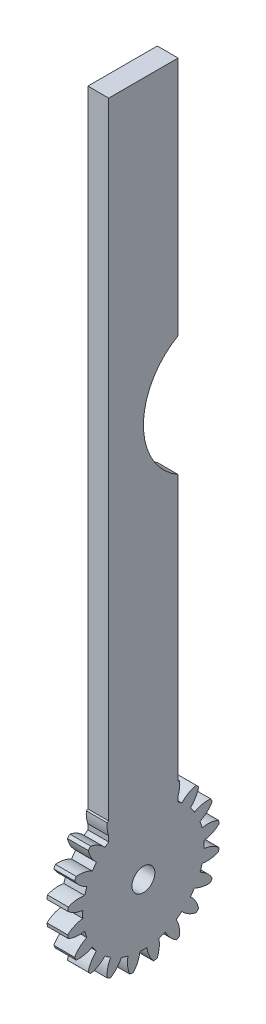
SolidWorks part; units mm, degrees
ref_plane "Plane1" through (0, 0, 0) normal (0, 0, 1) x (1, 0, 0)
ref_plane "Plane2" through (0, 0, 0) normal (0, 1, 0) x (1, 0, 0)
ref_plane "Plane3" through (0, 0, 0) normal (1, 0, 0) x (0, 0, -1)
sketch "HoldingSke" plane through (0, 0, 0) normal (0, 1, 0) x (1, 0, 0)
  line L0 (0, 0) -> (0.9397, -0.342)
  line L1 (-15, 0) -> (100, 0) construction
  line L2 (0, 0) -> (-2.1039, 2.3779)
  line L3 (0, 0) -> (-11.863, 4.5341)
  line L4 (0, 0) -> (8.1152, 2.9537)
  line L5 (0, 0) -> (-46.8476, -17.4728)
  line L6 (0, 0) -> (-2.4869, -1.6779)
  line L7 (-2.1039, 2.3779) -> (8.6586, 51.2059)
  line L8 (-76.2, 54.61) -> (-75.3, 54.61)
  line L9 (-71.009, 38.7566) -> (-53.1078, 45.2721)
  line L10 (-76.2, 71.12) -> (104.1128, 71.12)
  line L11 (0, 0) -> (-3, 0)
  line L12 (-76.2, 101.6) -> (-76.162, 101.6)
  line L13 (24.9733, 27.94) -> (52.9518, 28.4284)
  line L14 (24.9733, 27.94) -> (24.9743, 27.94)
  line L15 (24.9733, 27.94) -> (100.4006, 29.5858)
  line L16 (-63.627, -1) -> (-12.827, -1)
  circle A0 centre (0, 0) radius 2.5
  circle A1 centre (0, 0) radius 8.749
  circle A2 centre (0, 0) radius 37.5
  circle A3 centre (0, 0) radius 2.5
  dimension "MHD" = 17.498
  dimension "Hub_dia" = 75
  dimension "Bore" = 5
  dimension "MBD" = 5
  dimension "Num_teeth" = 20
  dimension "Pitch" = 1
  dimension "Overall_len" = 50
  dimension "Show_teeth" = 20
  dimension "Thickness" = 3
  dimension "OAL" = 50.0001
  dimension "T_dim" = 0.9
  dimension "Ap" = 20
  dimension "H" = 19.05
  dimension "Pitch_radius" = 180.3128
  dimension "Width" = 3
  dimension "Backlash" = 0.038
  dimension "Addendum_fac" = 1
  dimension "Dedendum_fac" = 1.25
  dimension "Clearance_fac" = 0.25
  dimension "Dedendum_add" = 0.001
  dimension "Module" = 1
sketch "BasProSke" plane through (0, 0, 0) normal (0, 1, 0) x (1, 0, 0)
  line L0 (-10, 0) -> (60, 0) construction
  line L1 (0, 0) -> (0, 11)
  line L2 (0, 0) -> (3, 0)
  line L3 (3, 0) -> (3, 11)
  line L4 (3, 11) -> (0, 11)
  dimension "Thickness" = 3
  dimension "Diameter" = 22
revolve "Base-Revolve" add sketch "BasProSke" angle 360 about L0
sketch "TooCutSke" plane through (0, 0, 0) normal (1, 0, 0) x (0, 0, -1)
  line L1 (0, 0) -> (0, 107) construction
  line L2 (0, 0) -> (-0.8511, 9.9637) construction
  line L3 (0, 0) -> (-3.1206, 19.7028) construction
  line L4 (-0.8511, 9.9637) -> (-1.5603, 9.8514) construction
  arc A0 (0.4999, 8.7347) -> (-0.4999, 8.7347) centre (0, 0) ccw
  arc A1 (1.4852, 10.9249) -> (-1.4852, 10.9249) centre (0, 0) ccw
  circle A2 centre (0, 0) radius 10 construction
  circle A3 centre (0, 0) radius 9.3969 construction
  arc A4 (-0.4999, 8.7347) -> (-1.4852, 10.9249) centre (-4.4722, 8.2645) ccw
  arc A5 (1.4852, 10.9249) -> (0.4999, 8.7347) centre (4.4722, 8.2645) ccw
  dimension "Root_dia" = 17.498
  dimension "Overcut_dia" = 22.0508
  dimension "Pitch_dia" = 20
  dimension "Base_dia" = 18.7939
  dimension "Flank_rad" = 4
  dimension "Half_ang" = 9
  dimension "Half_CT" = 0.7181
extrude "ToothCut" cut sketch "TooCutSke" along normal through all
fillet "Breaks" [suppressed] radius 0.02
fillet "RootFillets" [suppressed] radius 0.251
pattern_circular "TeethCuts" count 20 every 18 about axis through (-10, 0, 0) along (1, 0, 0) of "ToothCut", "RootFillets", "Breaks"
sketch "HubNeaOneSke" plane through (0, 0, 0) normal (-1, 0, 0) x (0, 0, 1)
  circle A0 centre (0, 0) radius 8.749
  dimension "Diameter" = 17.498
extrude "HubNearOne" [suppressed] add sketch "HubNeaOneSke" along normal blind 47.0001
sketch "HubNeaBotSke" plane through (0, 0, 0) normal (-1, 0, 0) x (0, 0, 1)
  circle A0 centre (0, 0) radius 8.749
  dimension "Diameter" = 17.498
extrude "HubNearBoth" [suppressed] add sketch "HubNeaBotSke" along normal blind 23.5
ref_plane "FarPln" through (3, 0, 0) normal (1, 0, 0) x (0, 0, -1)
sketch "HubFarSke" plane through (3, 0, 0) normal (1, 0, 0) x (0, 0, -1)
  circle A0 centre (0, 0) radius 8.749
  dimension "Diameter" = 17.498
extrude "HubFar" [suppressed] add sketch "HubFarSke" along normal blind 23.5
sketch "BorSke" plane through (0, 0, 0) normal (1, 0, 0) x (0, 0, -1)
  circle A0 centre (0, 0) radius 2.5
  dimension "Diameter" = 5
extrude "Bore" cut sketch "BorSke" along normal mid plane 100.0001
sketch "KeySke" plane through (0, 0, 0) normal (1, 0, 0) x (0, 0, -1)
  line L0 (-1, 0) -> (-1, 3.4)
  line L1 (-1, 3.4) -> (1, 3.4)
  line L2 (1, 3.4) -> (1, 0)
  line L3 (0, 0) -> (0, 34) construction
  line L4 (-1, 0) -> (1, 0)
  dimension "Offset" = 3.4
  dimension "Width" = 2
extrude "Keyway" [suppressed] cut sketch "KeySke" along normal mid plane 100.0001
pattern_circular "Keyway2" [suppressed] count 2 every 90 about axis through (-10, 0, 0) along (1, 0, 0)
sketch "Sketch1" plane through (3, 0, 0) normal (1, 0, 0) x (0, 0, -1)
  line L1 (-5, 0) -> (5, 0)
  line L2 (-5, 0) -> (-5, 100)
  line L3 (-5, 100) -> (5, 100)
  line L4 (5, 0) -> (5, 100)
  dimension "D1" = 10
  dimension "D2" = 100
extrude "Boss-Extrude1" add sketch "Sketch1" against normal blind 3
sketch "Sketch4" plane through (3, 0, 0) normal (1, 0, 0) x (0, 0, -1)
  line L0 (5, 9.798) -> (5, 100) construction
  line L1 (5, 65.3529) -> (5, 48.0324)
  arc A0 (5, 65.3529) -> (5, 48.0324) centre (10, 56.6927) ccw
  dimension "D1" = 5
extrude "Cut-Extrude1" cut sketch "Sketch4" against normal blind 3
sketch "Sketch5" plane through (3, 0, 0) normal (1, 0, 0) x (0, 0, -1)
  line L0 (-2.5, 0) -> (2.5, 0) construction
  line L1 (2.5, 0) -> (-2.5, 0)
  arc A0 (-2.5, 0) -> (2.5, 0) centre (0, 0) cw
extrude "Cut-Extrude2" cut sketch "Sketch5" against normal blind 3
sketch "Sketch6" plane through (3, 0, 0) normal (1, 0, 0) x (0, 0, -1)
  circle A0 centre (0, 0) radius 2.5
  circle A1 centre (0, 0) radius 1.65
extrude "Boss-Extrude2" add sketch "Sketch6" against normal blind 3
equation "' \"Module@HoldingSke\" = 6.35"
equation "' \"Num_teeth@HoldingSke\" = 12"
equation "' \"Ap@HoldingSke\" =  20"
equation "' \"Ap@HoldingSke\" = 20"
equation "' \"Width@HoldingSke\" = 0.5 * 25.4"
equation "' \"Hub_dia@HoldingSke\"= 1 * 25.4"
equation "' \"Hub_dia@HoldingSke\" = 1 * 25.4"
equation "' \"Overall_len@HoldingSke\" = 1.0 * 25.4"
equation "' \"Bore@HoldingSke\" = 0.75 * 25.4"
equation "' \"T_dim@HoldingSke\" = 0.1 * 25.4"
equation "' \"Width@KeySke\" = 0.25 * 25.4"
equation "' \"Show_teeth@HoldingSke\" = 13"
equation "' \"Backlash@HoldingSke\" = 0.009 * 25.4"
equation "' \"Addendum_fac@HoldingSke\" = 1.0"
equation "' \"Dedendum_fac@HoldingSke\" = 1.25"
equation "' \"Dedendum_add@HoldingSke\" = 0.00005 * 25.4"
equation "' \"Clearance_fac@HoldingSke\" = 0.25"
equation "\"Pitch@HoldingSke\" = 1 / \"Module@HoldingSke\""
equation "\"Overcut_dia@TooCutSke\" = (\"Num_teeth@HoldingSke\" + 2 * \"Addendum_fac@HoldingSke\") / \"Pitch@HoldingSke\" + 0.002 * 25.4"
equation "\"Pitch_dia@TooCutSke\" = \"Num_teeth@HoldingSke\" / \"Pitch@HoldingSke\""
equation "\"Base_dia@TooCutSke\" = \"Num_teeth@HoldingSke\" / \"Pitch@HoldingSke\" * cos((\"Ap@HoldingSke\"  * 3.14159265 / 180))"
equation "\"Root_dia@TooCutSke\" = (\"Num_teeth@HoldingSke\" + 2) / \"Pitch@HoldingSke\" - 2 * (\"Addendum_fac@HoldingSke\" + \"Dedendum_fac@HoldingSke\") / \"Pitch@HoldingSke\" - \"Dedendum_add@HoldingSke\" * 2"
equation "\"Half_ang@TooCutSke\" = 180 / \"Num_teeth@HoldingSke\""
equation "\"Half_CT@TooCutSke\" = \"Num_teeth@HoldingSke\" / \"Pitch@HoldingSke\" * sin((3.14159265 / 2 / \"Num_teeth@HoldingSke\")) / 2 - 7 * \"Backlash@HoldingSke\" / 4"
equation "\"Flank_rad@TooCutSke\" = \"Num_teeth@HoldingSke\" / \"Pitch@HoldingSke\" / 5"
equation "\"Radius@RootFillets\" = \"Clearance_fac@HoldingSke\" / \"Pitch@HoldingSke\" + \"Dedendum_add@HoldingSke\""
equation "\"Break_rad@Breaks\" = 0.02 / \"Pitch@HoldingSke\""
equation "\"Thickness@HoldingSke\" = \"Width@HoldingSke\""
equation "\"OAL@HoldingSke\" = \"Thickness@HoldingSke\""
equation "\"MHD@HoldingSke\" = (\"Num_teeth@HoldingSke\" + 2) / \"Pitch@HoldingSke\" - 2 * (\"Addendum_fac@HoldingSke\" + \"Dedendum_fac@HoldingSke\")  / \"Pitch@HoldingSke\" - \"Dedendum_add@HoldingSke\" * 2"
equation "\"MBD@HoldingSke\" = (\"Num_teeth@HoldingSke\" + 2) / \"Pitch@HoldingSke\" - 2 * (\"Addendum_fac@HoldingSke\" + \"Dedendum_fac@HoldingSke\")  / \"Pitch@HoldingSke\" - \"Dedendum_add@HoldingSke\" * 2 - 0.002 * 25.4"
equation "\"MHD@HoldingSke\" = ((sgn( \"MHD@HoldingSke\" - \"Hub_dia@HoldingSke\" )-1)*( \"MHD@HoldingSke\" - \"Hub_dia@HoldingSke\" ))/-2+ \"Hub_dia@HoldingSke\""
equation "\"MBD@HoldingSke\" = ((sgn( \"MBD@HoldingSke\" - \"Bore@HoldingSke\" )-1)*( \"MBD@HoldingSke\" - \"Bore@HoldingSke\" ))/-2+ \"Bore@HoldingSke\""
equation "\"OAL@HoldingSke\" = ((sgn( \"OAL@HoldingSke\" - \"Overall_len@HoldingSke\" )+1)*( \"OAL@HoldingSke\" - \"Overall_len@HoldingSke\" ))/2 + \"Overall_len@HoldingSke\" + 0.000002 * 25.4"
equation "\"Num_teeth@TeethCuts\" = int( \"Show_teeth@HoldingSke\" ) + 1"
equation "\"Num_teeth@TeethCuts\" = ((sgn( \"Num_teeth@TeethCuts\" - \"Num_teeth@HoldingSke\" )-1)*( \"Num_teeth@TeethCuts\" - \"Num_teeth@HoldingSke\" ))/-2+ \"Num_teeth@HoldingSke\""
equation "\"Num_teeth@TeethCuts\" = ((sgn( \"Num_teeth@TeethCuts\" - 2.0)+1)*( \"Num_teeth@TeethCuts\" - 2.0))/2 +2.0"
equation "\"Angle@TeethCuts\" = 360.0 / \"Num_teeth@HoldingSke\""
equation "\"Diameter@BasProSke\" = (\"Num_teeth@HoldingSke\" + 2 * \"Addendum_fac@HoldingSke\") / \"Pitch@HoldingSke\""
equation "\"Thickness@BasProSke\"  = \"Thickness@HoldingSke\""
equation "' \"Fillet_rad@BasProSke\" =  \"Thickness@HoldingSke\" * 0.05"
equation "' \"Fillet_rad@BasProSke\" = \"Thickness@HoldingSke\" * 0.05"
equation "\"MHD@HoldingSke\" = ((sgn( \"MHD@HoldingSke\" - \"Root_dia@TooCutSke\" )-1)*( \"MHD@HoldingSke\" - \"Root_dia@TooCutSke\" ))/-2+ \"Root_dia@TooCutSke\""
equation "\"Diameter@HubNeaOneSke\" = \"MHD@HoldingSke\""
equation "\"Length@HubNearOne\" = \"OAL@HoldingSke\" - \"Thickness@BasProSke\""
equation "\"Diameter@HubNeaBotSke\" = \"MHD@HoldingSke\""
equation "\"Length@HubNearBoth\" = ( \"OAL@HoldingSke\" - \"Thickness@BasProSke\" ) / 2.0"
equation "\"Thickness@FarPln\" = \"Thickness@BasProSke\""
equation "\"Diameter@HubFarSke\" = \"MHD@HoldingSke\""
equation "\"Length@HubFar\" = ( \"OAL@HoldingSke\" - \"Thickness@BasProSke\" ) / 2.0"
equation "\"Diameter@BorSke\" = \"MBD@HoldingSke\""
equation "\"D1@Bore\" = \"OAL@HoldingSke\" * 2.0"
equation "\"D1@Keyway\" = \"OAL@HoldingSke\" * 2.0"
equation "\"Offset@KeySke\" = \"T_dim@HoldingSke\" + \"MBD@HoldingSke\" / 2.0"
